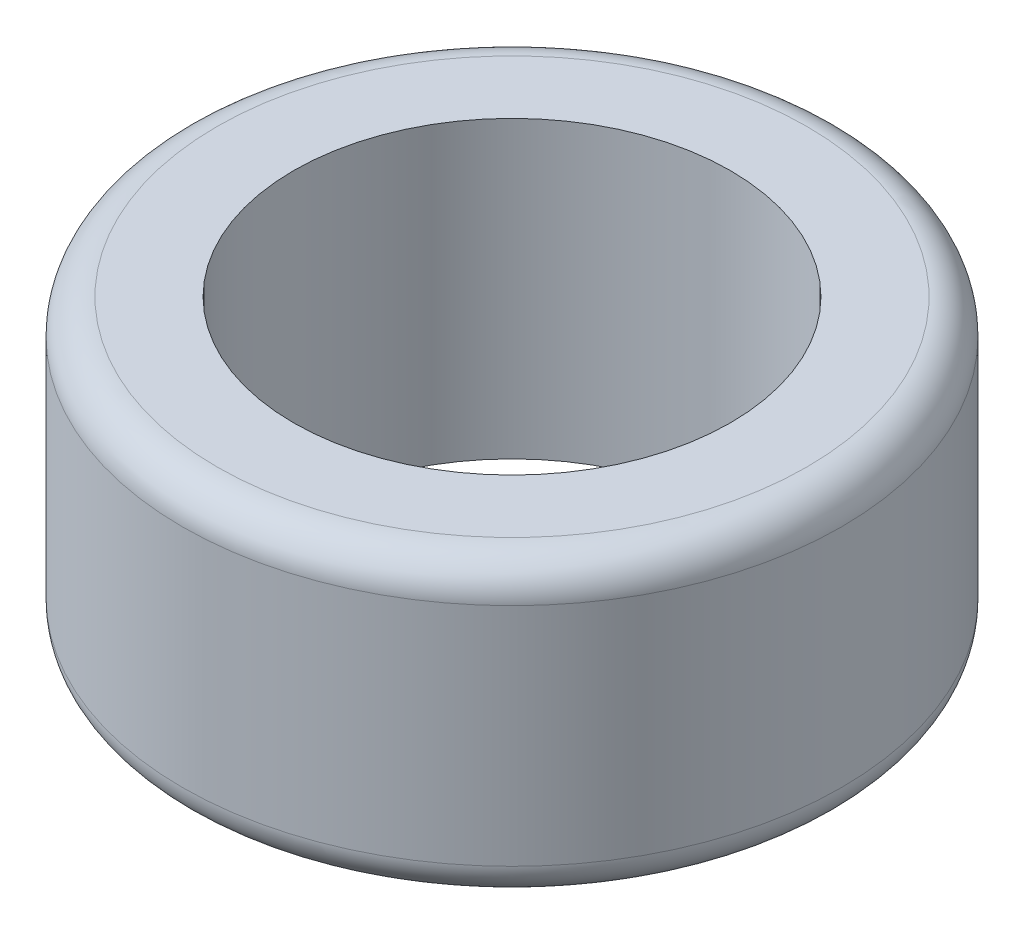
SolidWorks part; units mm, degrees
ref_plane "Front Plane" through (0, 0, 0) normal (0, 0, 1) x (1, 0, 0)
ref_plane "Top Plane" through (0, 0, 0) normal (0, 1, 0) x (1, 0, 0)
ref_plane "Right Plane" through (0, 0, 0) normal (1, 0, 0) x (0, 0, -1)
sketch "Sketch4" plane through (0, 0, 0) normal (0, 0, 1) x (1, 0, 0)
  line L0 (-152.4, 0) -> (-152.4, 205.74)
  line L1 (-152.4, 205.74) -> (-205.74, 205.74)
  line L2 (-152.4, 0) -> (-205.74, 0)
  line L3 (-229.87, 181.61) -> (-229.87, 24.13)
  line L4 (-152.4, 102.87) -> (-204.0709, 102.87) construction
  line L5 (0, 0) -> (0, 160.7909) construction
  arc A0 (-205.74, 205.74) -> (-229.87, 181.61) centre (-205.74, 181.61) ccw
  arc A1 (-229.87, 24.13) -> (-205.74, 0) centre (-205.74, 24.13) ccw
  point P11 (-229.87, 102.87)
  point P14 (-177.8439, 0)
  point P15 (-200.9466, 0)
  dimension "D1" = 205.74
  dimension "D2" = 157.48
  dimension "D3" = 229.87
  dimension "D4" = 152.4
revolve "Revolve1" add sketch "Sketch4" angle 360 about L5
ref_plane "Plane2" through (0, 102.87, 0) normal (0, -1, 0) x (-1, 0, 0)
